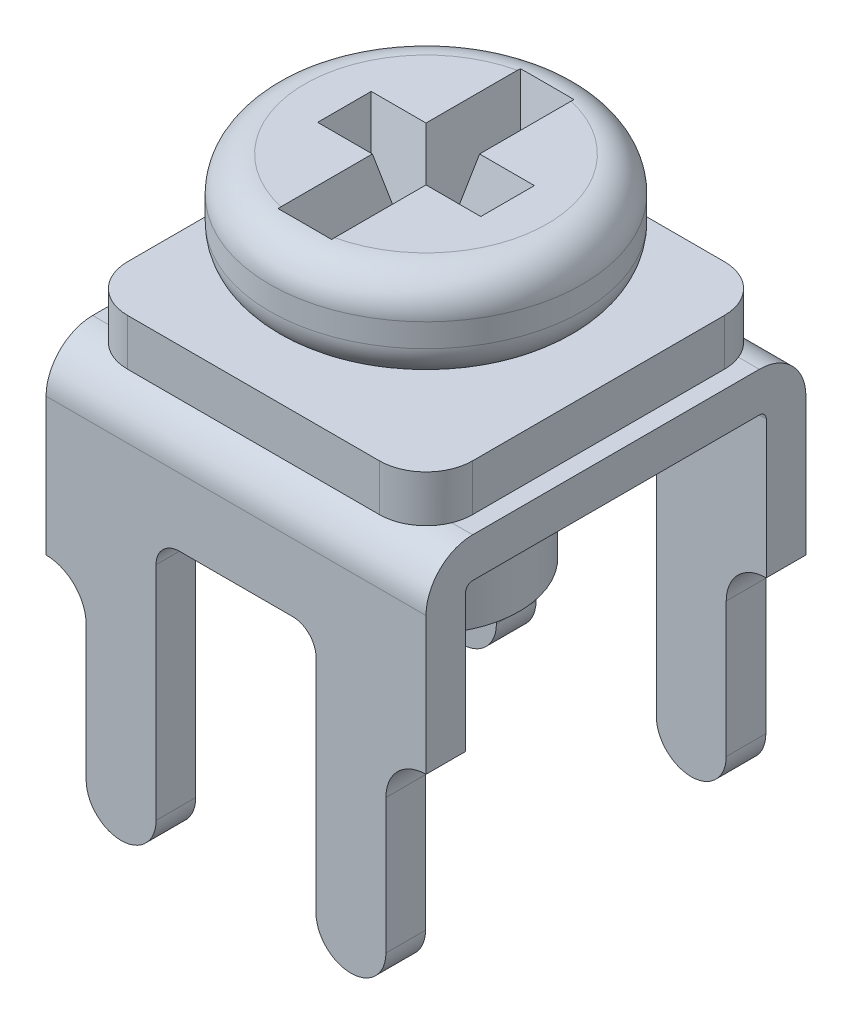
SolidWorks part; units mm, degrees
ref_plane "Front Plane" through (0, 0, 0) normal (0, 0, 1) x (1, 0, 0)
ref_plane "Top Plane" through (0, 0, 0) normal (0, 1, 0) x (1, 0, 0)
ref_plane "Right Plane" through (0, 0, 0) normal (1, 0, 0) x (0, 0, -1)
sketch "Sketch1" plane through (0, 0, 0) normal (1, 0, 0) x (0, 0, -1)
  line L0 (0, 39.8206) -> (0, -23.5518) construction
  line L1 (-3.075, 4.725) -> (3.075, 4.725)
  line L2 (4.075, 3.725) -> (4.075, -3.725)
  line L3 (-4.075, 3.725) -> (-4.075, -3.725)
  arc A0 (4.075, 3.725) -> (3.075, 4.725) centre (3.075, 3.725) ccw
  arc A1 (-4.075, 3.725) -> (-3.075, 4.725) centre (-3.075, 3.725) cw
  point P8 (4.075, 4.725)
  point P9 (4.075, 0)
  point P14 (0, 4.725)
  dimension "D3" = 1
  dimension "D1" = 8.15
  dimension "D2" = 8.45
extrude "Extrude-Thin1" add sketch "Sketch1" along normal mid plane 8.15 thin
sketch "Sketch3" plane through (0, 0, 0) normal (0, 0, 1) x (1, 0, 0)
  line L0 (4.075, -3.725) -> (-4.075, -3.725) construction
  line L1 (-1.715, -3.725) -> (1.715, -3.725)
  line L2 (-1.715, -2.975) -> (-1.715, 1.775)
  line L3 (-1.215, 2.275) -> (1.215, 2.275)
  line L4 (1.715, -2.975) -> (1.715, 1.775)
  line L5 (-1.715, -3.725) -> (1.715, 2.275) construction
  line L6 (-1.715, 2.275) -> (1.715, -3.725) construction
  line L7 (3.215, -2.975) -> (3.215, -0.085)
  line L8 (4.075, 3.725) -> (4.075, -3.725) construction
  line L9 (4.075, 0.775) -> (4.075, -3.725)
  line L10 (4.075, -3.725) -> (3.215, -3.725)
  line L11 (0, 0) -> (0, -2.5996) construction
  line L12 (-4.075, -3.725) -> (-3.215, -3.725)
  line L13 (-4.075, 0.775) -> (-4.075, -3.725)
  line L14 (-3.215, -2.975) -> (-3.215, -0.085)
  line L15 (3.215, -3.725) -> (3.215, -2.975) construction
  line L16 (1.715, -3.725) -> (1.715, -2.975) construction
  line L17 (3.215, -3.725) -> (3.215, -3.9728)
  line L18 (3.215, -3.9728) -> (1.715, -3.9728)
  line L19 (1.715, -3.9728) -> (1.715, -3.725)
  line L20 (-3.215, -3.725) -> (-3.215, -3.9728)
  line L21 (-3.215, -3.9728) -> (-1.715, -3.9728)
  line L22 (-1.715, -3.9728) -> (-1.715, -3.725)
  line L23 (-3.215, -3.725) -> (-3.215, -2.975) construction
  line L24 (-1.715, -3.725) -> (-1.715, -2.975) construction
  arc A0 (1.215, 2.275) -> (1.715, 1.775) centre (1.215, 1.775) cw
  arc A1 (-1.715, 1.775) -> (-1.215, 2.275) centre (-1.215, 1.775) cw
  arc A2 (3.215, -0.085) -> (4.075, 0.775) centre (4.075, -0.085) cw
  arc A3 (-3.215, -0.085) -> (-4.075, 0.775) centre (-4.075, -0.085) ccw
  arc A4 (1.715, -2.975) -> (3.215, -2.975) centre (2.465, -2.975) ccw
  arc A5 (-1.715, -2.975) -> (-3.215, -2.975) centre (-2.465, -2.975) cw
  point P0 (0, -0.725)
  point P8 (0, -3.725)
  dimension "D3" = 0.5
  dimension "D4" = 1.5
  dimension "D1" = 6
  dimension "D2" = 3.43
  dimension "D5" = 4.5
extrude "Cut-Extrude1" cut sketch "Sketch3" against normal through all both and the other way through all
sketch "Sketch4" plane through (0, 4.725, 0) normal (0, 1, 0) x (1, 0, 0)
  line L1 (-2.7, -3.7) -> (2.7, -3.7)
  line L2 (-3.7, -2.7) -> (-3.7, 2.7)
  line L3 (-2.7, 3.7) -> (2.7, 3.7)
  line L4 (3.7, -2.7) -> (3.7, 2.7)
  line L5 (-3.7, -3.7) -> (3.7, 3.7) construction
  line L6 (-3.7, 3.7) -> (3.7, -3.7) construction
  arc A0 (2.7, 3.7) -> (3.7, 2.7) centre (2.7, 2.7) cw
  arc A1 (3.7, -2.7) -> (2.7, -3.7) centre (2.7, -2.7) cw
  arc A2 (-3.7, -2.7) -> (-2.7, -3.7) centre (-2.7, -2.7) ccw
  arc A3 (-3.7, 2.7) -> (-2.7, 3.7) centre (-2.7, 2.7) cw
  point P0 (0, 0)
  dimension "D2" = 1
  dimension "D1" = 7.4
extrude "Boss-Extrude1" add sketch "Sketch4" along normal blind 1
sketch "Sketch5" plane through (0, 5.725, 0) normal (0, 1, 0) x (1, 0, 0)
  circle A0 centre (0, 0) radius 2
  dimension "D1" = 4
extrude "Boss-Extrude2" add sketch "Sketch5" along normal blind 0.5 and the other way blind 5
sketch "Sketch6" plane through (0, 6.225, 0) normal (0, 1, 0) x (1, 0, 0)
  circle A0 centre (0, 0) radius 3.35
  dimension "D1" = 6.7
extrude "Boss-Extrude3" add sketch "Sketch6" along normal blind 2
fillet "Fillet1" radius 0.75 2 edges at (0, 6.225, 3.35) (0, 8.225, 3.35)
sketch "Sketch7" plane through (0, 8.225, 0) normal (0, 1, 0) x (1, 0, 0)
  line L0 (0, 2.6) -> (0, -2.6)
  line L1 (1.75, 0) -> (-1.75, 0)
  circle A0 centre (0, 0) radius 2.6 construction
  point P8 (0, 0)
extrude "Cut-Extrude-Thin1" cut sketch "Sketch7" against normal blind 2 draft 13 thin thin type mid plane wall 1.15
